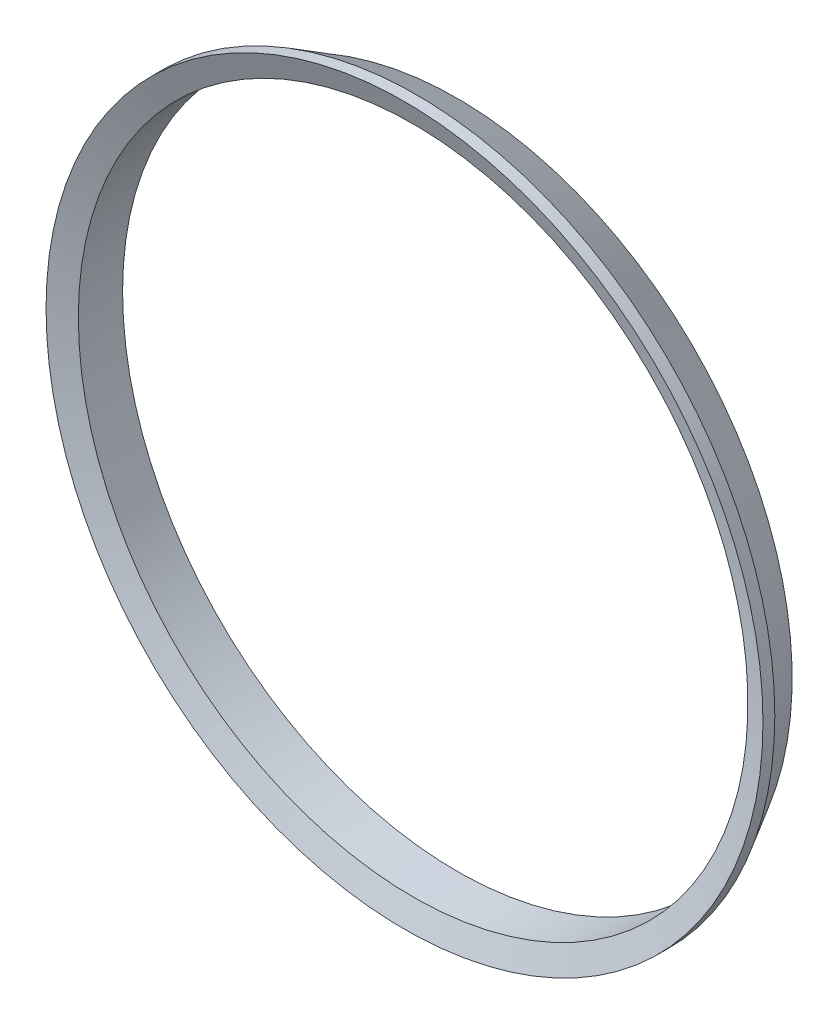
SolidWorks part; units mm, degrees
ref_plane "Front Plane" through (0, 0, 0) normal (1, 0, 0) x (0, 1, 0)
ref_plane "Top Plane" through (0, 0, 0) normal (0, 0, 1) x (0, 1, 0)
ref_plane "Right Plane" through (0, 0, 0) normal (0, 1, 0) x (-1, 0, 0)
sketch "Sketch1" plane through (0, 0, 0) normal (1, 0, 0) x (0, 1, 0)
  line L0 (0, 0) -> (0, 133.1878) construction
  line L1 (-141.4, 1.3603) -> (-151.4, 5)
  line L2 (-151.4, 5) -> (-151.4, 0)
  line L3 (-151.4, 0) -> (-141.4, -17.3205)
  line L4 (-141.4, -17.3205) -> (-141.4, 1.3603)
  point P5 (-142.4, 6.3609)
  point P8 (0, 0)
  point P9 (0, 0)
  point P10 (0, 0)
  dimension "D1" = 302.8
  dimension "D2" = 10
  dimension "D3" = 70
  dimension "D4" = 30
  dimension "D5" = 5
revolve "Revolve1" add sketch "Sketch1" angle 360 about L0
